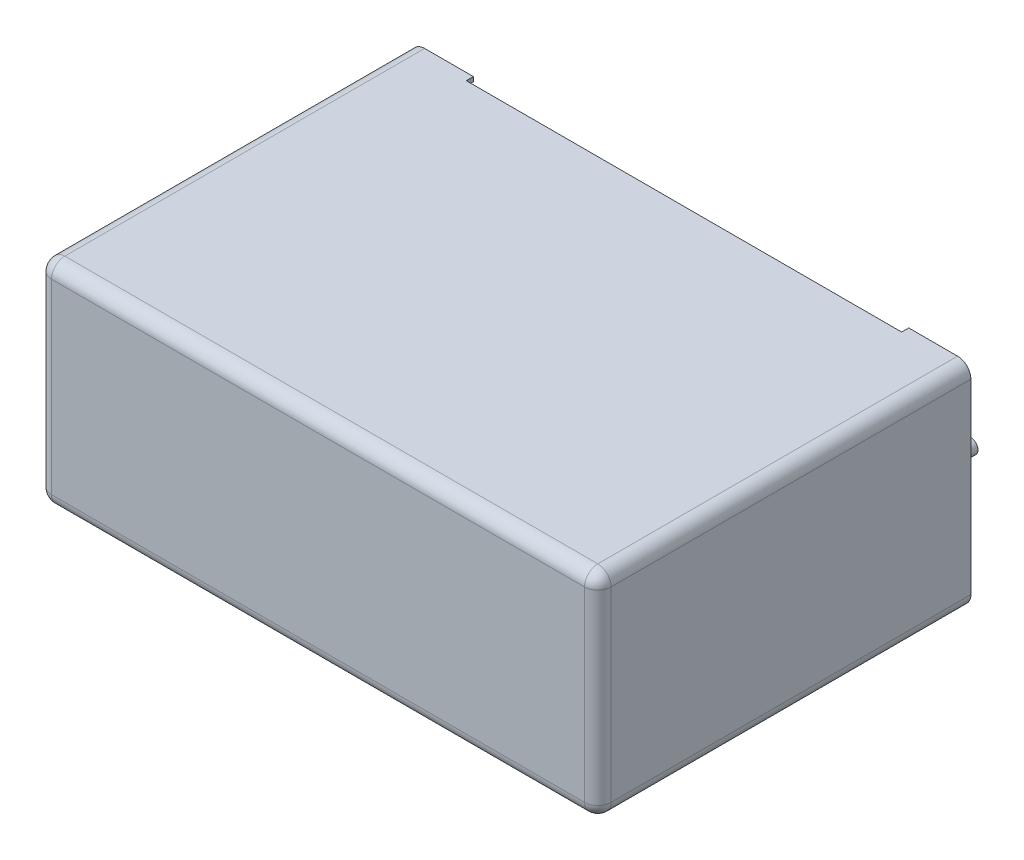
SolidWorks part; units mm, degrees
material "Duranickel(R) 301"
ref_plane "Front Plane" through (0, 0, 0) normal (0, 0, 1) x (1, 0, 0)
ref_plane "Top Plane" through (0, 0, 0) normal (0, 1, 0) x (1, 0, 0)
ref_plane "Right Plane" through (0, 0, 0) normal (1, 0, 0) x (0, 0, -1)
sketch "Sketch1" plane through (0, 0, 0) normal (0, 0, 1) x (1, 0, 0)
  line L1 (15.75, 6) -> (-15.75, 6)
  line L2 (15.75, 6) -> (15.75, -6)
  line L3 (15.75, -6) -> (-15.75, -6)
  line L4 (-15.75, 6) -> (-15.75, -6)
  line L5 (15.75, 6) -> (-15.75, -6) construction
  line L6 (15.75, -6) -> (-15.75, 6) construction
  point P0 (0, 0)
  dimension "D1" = 31.5
  dimension "D2" = 12
extrude "Extrude1" add sketch "Sketch1" along normal blind 21
fillet "Fillet1" radius 0.75 8 edges at (15.75, 6, 10.5) (15.75, -6, 10.5) (15.75, 0, 21) (0, 6, 21) (0, -6, 21) (-15.75, -6, 10.5) (-15.75, 6, 10.5) (-15.75, 0, 21)
sketch "Sketch3" plane through (0, -6, 0) normal (0, -1, 0) x (1, 0, 0)
  line L0 (-9, 14.2477) -> (9, 14.2477) construction
  text T0 "MKP X2 \r\n470nF \r\n250V AC" font "Century Gothic" height in points 6
extrude "Boss-Extrude1" add sketch "Sketch3" along normal blind 0.01
sketch "Sketch4" plane through (0, 0, 0) normal (0, 0, -1) x (-1, 0, 0)
  line L0 (-15.75, -5.25) -> (-15.75, 5.25) construction
  line L1 (-15.5, 5.75) -> (15.5, 5.75)
  line L2 (-15.5, 5.75) -> (-15.5, -5.75)
  line L3 (-15.5, -5.75) -> (15.5, -5.75)
  line L4 (15.5, 5.75) -> (15.5, -5.75)
  line L5 (-15.5, 5.75) -> (15.5, -5.75) construction
  line L6 (-15.5, -5.75) -> (15.5, 5.75) construction
  line L7 (-15, 6) -> (15, 6) construction
  point P0 (0, 0)
  dimension "D1" = 0.25
  dimension "D2" = 0.25
extrude "Cut-Extrude1" cut sketch "Sketch4" against normal blind 0.5
sketch "Sketch5" plane through (0, -6, 0) normal (0, -1, 0) x (1, 0, 0)
  line L0 (-15, 0) -> (15, 0) construction
  line L1 (-12.25, 0) -> (12.25, 0) construction
  line L2 (-12.25, 0) -> (-12.25, 0.4)
  line L3 (-12.25, 0.4) -> (12.25, 0.4)
  line L4 (12.25, 0) -> (12.25, 0.4)
  line L5 (-15.75, 0) -> (-15.75, 20.25) construction
  point P6 (0, 0)
  dimension "D1" = 0.4
  dimension "D2" = 3.5
extrude "Cut-Extrude5" cut sketch "Sketch5" against normal blind 12 and the other way through all
sketch "Sketch2" plane through (0, 0, 0.5) normal (0, 0, -1) x (-1, 0, 0)
  line L0 (-13.75, 0) -> (13.75, 0) construction
  circle A0 centre (-13.75, 0) radius 0.4
  circle A1 centre (13.75, 0) radius 0.4
  point P0 (0, 0)
  dimension "D1" = 0.8
  dimension "D2" = 27.5
extrude "Extrude2" add sketch "Sketch2" along normal blind 2.5
